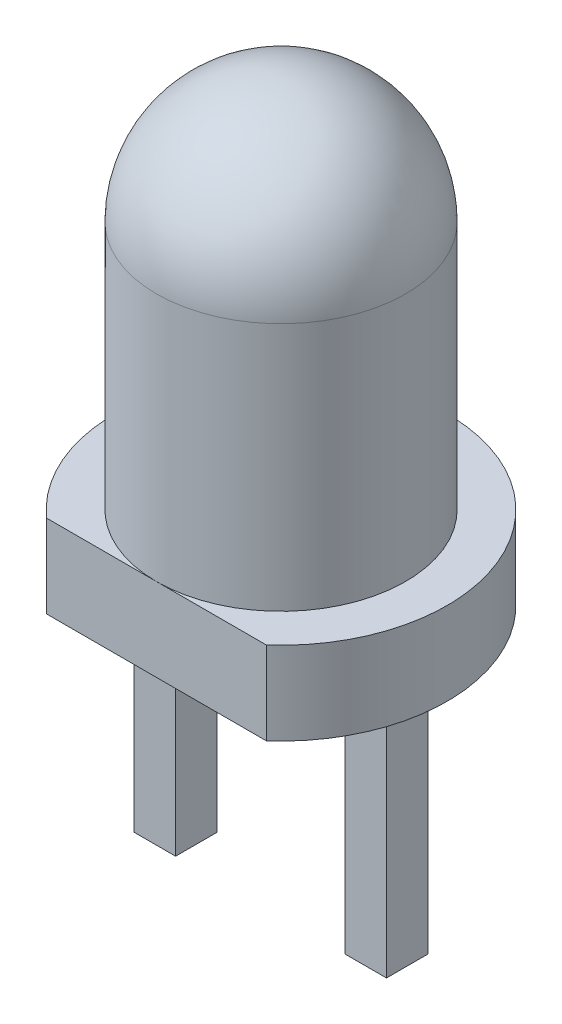
SolidWorks part; units mm, degrees
ref_plane "Front Plane" through (0, 0, 0) normal (0, 0, 1) x (1, 0, 0)
ref_plane "Top Plane" through (0, 0, 0) normal (0, 1, 0) x (1, 0, 0)
ref_plane "Right Plane" through (0, 0, 0) normal (1, 0, 0) x (0, 0, -1)
sketch "Sketch1" plane through (0, 0, 0) normal (1, 0, 0) x (0, 0, -1)
  line L0 (-1.5, 0) -> (-1.5, 3.5)
  line L1 (0, 5) -> (0, 0) construction
  line L2 (0, 0) -> (-1.5, 0)
  line L3 (0, 5) -> (0, 0)
  arc A0 (-1.5, 3.5) -> (0, 5) centre (0, 3.5) cw
  point P4 (0, 0)
  dimension "D1" = 3
  dimension "D2" = 5
revolve "Revolve1" add sketch "Sketch1" angle 360 about L1
sketch "Sketch2" plane through (0, 0, 0) normal (0, 1, 0) x (1, 0, 0)
  line L0 (-1.3229, -1.5) -> (1.3229, -1.5)
  arc A0 (1.3229, -1.5) -> (-1.3229, -1.5) centre (0, 0) ccw
  circle A1 centre (0, 0) radius 1.5 construction
  dimension "D1" = 4
extrude "Boss-Extrude1" add sketch "Sketch2" along normal mid plane 1
sketch "Sketch3" plane through (0, -0.5, 0) normal (0, -1, 0) x (1, 0, 0)
  line L1 (-1.52, 0.25) -> (-1.02, 0.25)
  line L2 (-1.52, 0.25) -> (-1.52, -0.25)
  line L3 (-1.52, -0.25) -> (-1.02, -0.25)
  line L4 (-1.02, 0.25) -> (-1.02, -0.25)
  line L5 (1.02, 0.25) -> (1.52, 0.25)
  line L6 (1.02, 0.25) -> (1.02, -0.25)
  line L7 (1.02, -0.25) -> (1.52, -0.25)
  line L8 (1.52, 0.25) -> (1.52, -0.25)
  point P8 (-1.02, 0)
  point P9 (1.02, 0)
  point P11 (-1.27, 0.25)
  point P12 (1.27, 0.25)
  dimension "D1" = 0.5
  dimension "D2" = 2.54
  dimension "D3" = 1.27
extrude "Boss-Extrude2" add sketch "Sketch3" along normal blind 3 separate body
